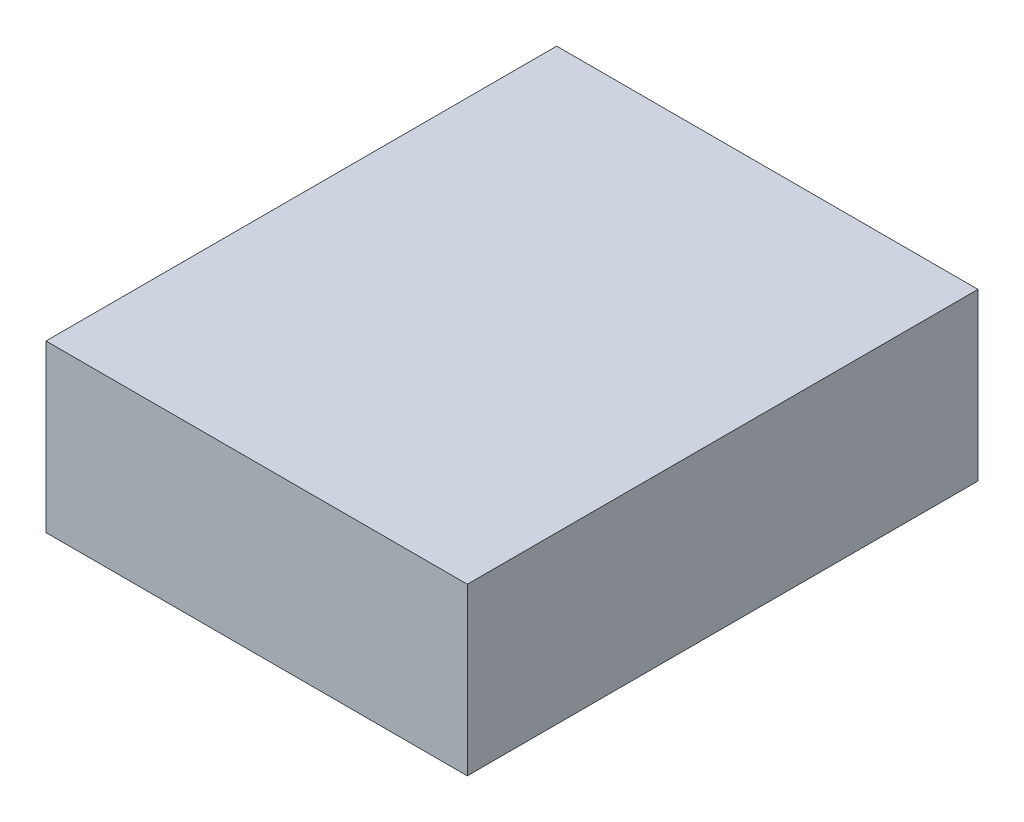
SolidWorks part; units mm, degrees
material "ABS"
ref_plane "Plan de face" through (0, 0, 0) normal (0, 0, 1) x (1, 0, 0)
ref_plane "Plan de dessus" through (0, 0, 0) normal (0, 1, 0) x (1, 0, 0)
ref_plane "Plan de droite" through (0, 0, 0) normal (1, 0, 0) x (0, 0, -1)
sketch "Esquisse1" plane through (0, 0, 0) normal (0, 0, 1) x (1, 0, 0)
  line L1 (-3.3, -1.3) -> (3.3, -1.3)
  line L2 (-3.3, -1.3) -> (-3.3, 1.3)
  line L3 (-3.3, 1.3) -> (3.3, 1.3)
  line L4 (3.3, -1.3) -> (3.3, 1.3)
  line L5 (-3.3, -1.3) -> (3.3, 1.3) construction
  line L6 (-3.3, 1.3) -> (3.3, -1.3) construction
  point P0 (0, 0)
  dimension "D1" = 6.6
  dimension "D2" = 2.6
extrude "Boss.-Extru.1" add sketch "Esquisse1" along normal blind 8
equation "\"entretoiseBearing\"= 1.5mm"
equation "\"length_tibia\"= 206mm"
equation "\"length_femur\"= 117mm"
equation "\"length_coxa\"= 27mm"
equation "\"height\"= 40mm"
equation "\"width\"= 100mm"
equation "\"lever\"= 40mm"
equation "\"errorFlat\"= 0.20mm"
equation "\"errorCircle\"= 0.40mm"
equation "\"cuticule\"=1.5mm"
equation "\"cuticule_attach_w\"=10mm"
equation "\"cuticule_attach_h\"=2.5mm"
equation "\"depthMagnet\"= 1mm"
equation "\"insert_d\" = 3.2mm"
equation "\"insert_l\" = 5mm"
equation "\"D1@Esquisse1\"=7 - \"errorFlat\"*2"
equation "\"D2@Esquisse1\"=3 - \"errorFlat\"*2"
equation "\"errorFlat_tight\"= 0.15mm"
equation "\"errorCircle_tight\" = 0.30mm"
